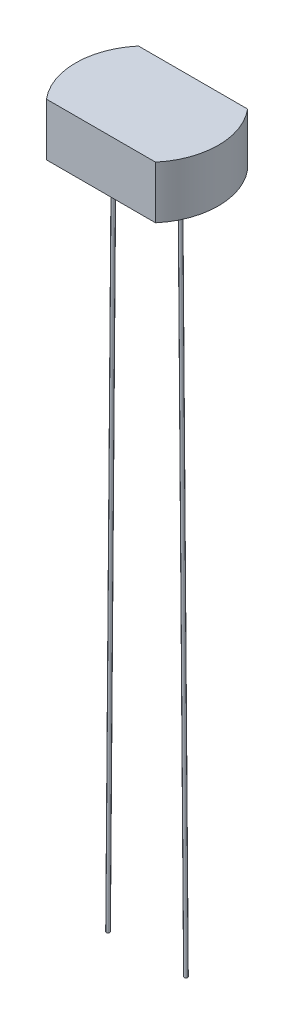
SolidWorks part; units mm, degrees
ref_plane "Front Plane" through (0, 0, 0) normal (0, 0, 1) x (1, 0, 0)
ref_plane "Top Plane" through (0, 0, 0) normal (0, 1, 0) x (1, 0, 0)
ref_plane "Right Plane" through (0, 0, 0) normal (1, 0, 0) x (0, 0, -1)
sketch "Sketch1" plane through (0, 0, 0) normal (0, 1, 0) x (1, 0, 0)
  line L0 (-2.075, 1.75) -> (2.075, 1.75)
  line L1 (-2.075, -1.75) -> (2.075, -1.75)
  line L2 (0, 0) -> (0, 1.75) construction
  line L3 (0, 0) -> (0, -1.75) construction
  arc A0 (-2.075, 1.75) -> (-2.075, -1.75) centre (0, 0) ccw
  arc A1 (2.075, -1.75) -> (2.075, 1.75) centre (0, 0) ccw
  dimension "D1" = 4.15
  dimension "D2" = 3.5
extrude "Boss-Extrude1" add sketch "Sketch1" along normal blind 2
sketch "Sketch2" plane through (0, 0, 0) normal (0, 0, 1) x (1, 0, 0)
  line L0 (-2.075, 0) -> (-2.286, -26)
  line L1 (2.075, 0) -> (2.286, -26)
  dimension "D1" = 26
  dimension "D2" = 26
  dimension "D3" = 2.286
  dimension "D4" = 2.286
sketch "Sketch3" plane through (0, 0, 0) normal (0, -1, 0) x (1, 0, 0)
  line L0 (-2.075, 0) -> (-2.286, 0) construction
  circle A0 centre (-1.27, 0) radius 0.0635
  dimension "D1" = 0.127
  dimension "D2" = 1.27
sweep "Sweep1" add profiles "Sketch3" path "Sketch2"
ref_plane "Plane1" through (0, 0, 0) normal (1, 0, 0) x (0, 0, -1)
mirror "Mirror1" about plane through (0, 0, 0) normal (1, 0, 0) of "Sweep1"
